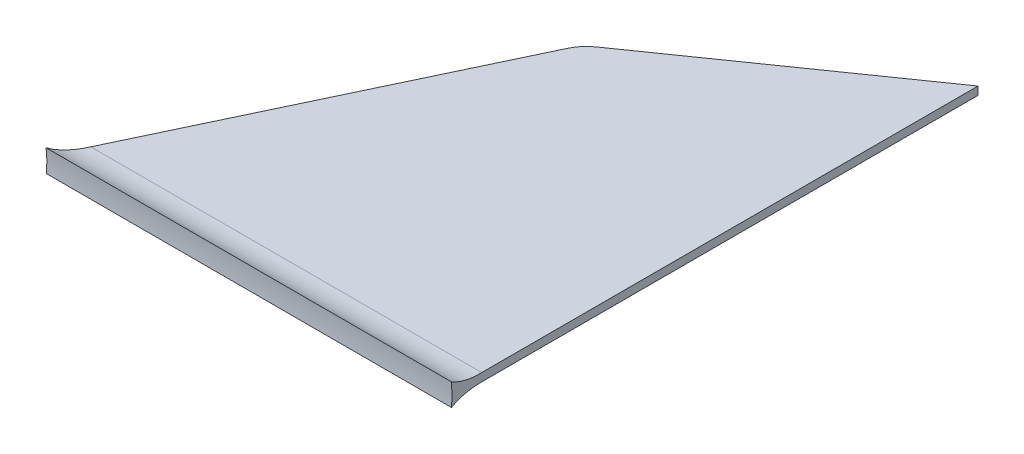
SolidWorks part; units mm, degrees
material "Plástico personalizado"
ref_plane "Plano frontal" through (0, 0, 0) normal (0, 0, 1) x (1, 0, 0)
ref_plane "Plano superior" through (0, 0, 0) normal (0, 1, 0) x (1, 0, 0)
ref_plane "Plano direito" through (0, 0, 0) normal (1, 0, 0) x (0, 0, -1)
sketch "Esboço1" plane through (0, 0, 0) normal (0, 1, 0) x (1, 0, 0)
  line L0 (0, 0) -> (100.1, 0)
  line L1 (100.1, 0) -> (100.1, 130.2)
  line L2 (100.1, 130.2) -> (42.5645, 90)
  line L3 (42.5645, 90) -> (0, 0)
  dimension "D1" = 100.1
  dimension "D2" = 130.2
  dimension "D3" = 90
  dimension "D4" = 90
extrude "Ressalto-extrusão1" add sketch "Esboço1" along normal blind 2
fillet "Filete1" radius 10 1 edges at (42.5645, 1, -90)
sketch "Esboço2" plane through (0, 0, 0) normal (0, -1, 0) x (-1, 0, 0)
  line L0 (-100.1, 0) -> (-100.1, 7.846)
  line L1 (-100.1, 0) -> (-100.1, 130.2) construction
  line L2 (-100.1, 7.846) -> (-3.7107, 7.846)
  line L3 (-41.429, 87.5991) -> (0, 0) construction
  line L4 (-3.7107, 7.846) -> (0, 0)
  line L5 (0, 0) -> (-100.1, 0)
extrude "Ressalto-extrusão2" add sketch "Esboço2" along normal blind 2 and the other way blind 4
sketch "Esboço4" plane through (100.1, 0, 0) normal (1, 0, 0) x (0, 0, -1)
  line L0 (0, 4) -> (7.846, 4)
  line L1 (7.846, 4) -> (7.846, 2)
  line L2 (7.846, 0) -> (7.846, -2)
  line L3 (7.846, -2) -> (0, -2)
  spline S0 degree 2 poles (7.846, 2) (3.1403, 1.9039) (0, 4) knots 0 0 0 1 1 1
  spline S1 degree 2 poles (7.846, 0) (3.1069, 0.0091) (0, -2) knots 0 0 0 1 1 1
extrude "Corte-extrusão1" cut sketch "Esboço4" against normal blind 106
sketch "Esboço5" plane through (100.1, 0, 0) normal (1, 0, 0) x (0, 0, -1)
  line L0 (0, 4) -> (0, -2) construction
  circle A0 centre (-32, 0.7324) radius 32.5
  dimension "D1" = 32
extrude "Corte-extrusão2" cut sketch "Esboço5" against normal blind 106
